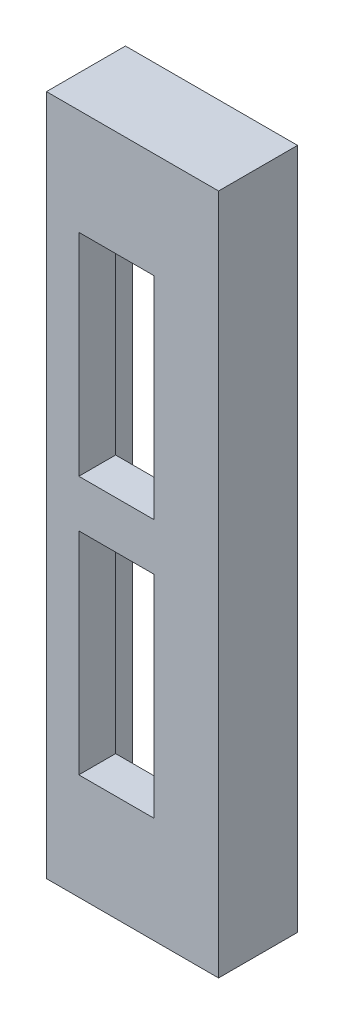
SolidWorks part; units mm, degrees
ref_plane "Front Plane" through (0, 0, 0) normal (0, 0, 1) x (1, 0, 0)
ref_plane "Top Plane" through (0, 0, 0) normal (0, 1, 0) x (1, 0, 0)
ref_plane "Right Plane" through (0, 0, 0) normal (1, 0, 0) x (0, 0, -1)
sketch "Sketch1" plane through (0, 0, 0) normal (0, 0, 1) x (1, 0, 0)
  line L4 (40, -50) -> (-40, -50)
  line L5 (40, 50) -> (40, -50)
  line L6 (-40, 50) -> (40, 50)
  line L7 (-40, -50) -> (-40, 50)
  line L8 (-39.25, -49.25) -> (-39.25, 49.25)
  line L9 (-39.25, 49.25) -> (39.25, 49.25)
  line L10 (39.25, 49.25) -> (39.25, -49.25)
  line L11 (39.25, -49.25) -> (-39.25, -49.25)
  line L12 (-16.5, 44.5) -> (-19.05, 38.013)
  line L13 (-16.5, 44.5) -> (16.5, 44.5)
  line L14 (16.5, 44.5) -> (19.05, 38.013)
  line L15 (-1000, 38.013) -> (49000, 38.013) construction
  line L16 (16.5, 31.526) -> (19.05, 38.013)
  line L17 (-16.5, 31.526) -> (16.5, 31.526)
  line L18 (-16.5, 31.526) -> (-19.05, 38.013)
  line L19 (-1000, 0.0306) -> (-26.3532, 0.0306) construction
  line L26 (-15.5, 43.5) -> (15.5, 43.5)
  line L27 (15.5, 43.5) -> (15.5, 32.5)
  line L28 (15.5, 32.5) -> (-15.5, 32.5)
  line L29 (-15.5, 32.5) -> (-15.5, 43.5)
  line L30 (15.5, -32.4388) -> (-15.5, -32.4388)
  line L31 (15.5, -43.4388) -> (15.5, -32.4388)
  line L32 (-15.5, -43.4388) -> (15.5, -43.4388)
  line L33 (-15.5, -32.4388) -> (-15.5, -43.4388)
  line L34 (-16.5, -31.4648) -> (16.5, -31.4648)
  line L35 (-16.5, -31.4648) -> (-19.05, -37.9518)
  line L36 (-16.5, -44.4388) -> (-19.05, -37.9518)
  line L37 (-16.5, -44.4388) -> (16.5, -44.4388)
  line L38 (16.5, -44.4388) -> (19.05, -37.9518)
  line L39 (16.5, -31.4648) -> (19.05, -37.9518)
  line L40 (-19.05, 0.0306) -> (-16.5, 6.5)
  line L41 (-16.5, 6.5) -> (16.5, 6.5)
  line L42 (16.5, 6.5) -> (19.05, 0.0306)
  line L43 (-15.5, 5.5) -> (-15.5, -5.5)
  line L44 (-15.5, -5.5) -> (15.5, -5.5)
  line L45 (15.5, -5.5) -> (15.5, 5.5)
  line L46 (15.5, 5.5) -> (-15.5, 5.5)
  line L47 (16.5, -6.4388) -> (19.05, 0.0306)
  line L48 (-16.5, -6.4388) -> (16.5, -6.4388)
  line L49 (-19.05, 0.0306) -> (-16.5, -6.4388)
  line L50 (-31.5, 35.5) -> (-25.0832, 38.05)
  line L51 (-25.0832, 38.05) -> (-18.5, 35.5)
  line L52 (-18.5, 35.5) -> (-18.5, 2.5)
  line L53 (-18.5, 2.5) -> (-23.8468, 0.429)
  line L55 (-31.5, 2.5) -> (-31.5, 35.5)
  line L56 (0, -999.9694) -> (0, 49000.0306) construction
  line L57 (-30.5, 34.5) -> (-19.5, 34.5)
  line L58 (-19.5, 34.5) -> (-19.5, 3.5)
  line L59 (-19.5, 3.5) -> (-30.5, 3.5)
  line L60 (-30.5, 3.5) -> (-30.5, 34.5)
  line L62 (18.5, 2.5) -> (23.8468, 0.429)
  line L63 (18.5, 35.5) -> (18.5, 2.5)
  line L64 (25.0832, 38.05) -> (18.5, 35.5)
  line L65 (31.5, 35.5) -> (25.0832, 38.05)
  line L66 (31.5, 2.5) -> (31.5, 35.5)
  line L67 (19.5, 3.5) -> (30.5, 3.5)
  line L68 (19.5, 34.5) -> (19.5, 3.5)
  line L69 (30.5, 34.5) -> (19.5, 34.5)
  line L70 (30.5, 3.5) -> (30.5, 34.5)
  line L71 (19.5, -34.4388) -> (19.5, -3.4388)
  line L72 (30.5, -34.4388) -> (19.5, -34.4388)
  line L73 (30.5, -3.4388) -> (30.5, -34.4388)
  line L74 (19.5, -3.4388) -> (30.5, -3.4388)
  line L75 (18.5, -2.4388) -> (23.8468, -0.3677)
  line L76 (18.5, -35.4388) -> (18.5, -2.4388)
  line L77 (25.0832, -37.9888) -> (18.5, -35.4388)
  line L78 (31.5, -35.4388) -> (25.0832, -37.9888)
  line L79 (31.5, -2.4388) -> (31.5, -35.4388)
  line L81 (-19.5, -3.4388) -> (-30.5, -3.4388)
  line L82 (-19.5, -34.4388) -> (-19.5, -3.4388)
  line L83 (-30.5, -34.4388) -> (-19.5, -34.4388)
  line L84 (-30.5, -3.4388) -> (-30.5, -34.4388)
  line L86 (-18.5, -2.4388) -> (-23.8468, -0.3677)
  line L87 (-18.5, -35.4388) -> (-18.5, -2.4388)
  line L88 (-25.0832, -37.9888) -> (-18.5, -35.4388)
  line L89 (-31.5, -35.4388) -> (-25.0832, -37.9888)
  line L90 (-31.5, -2.4388) -> (-31.5, -35.4388)
  line L91 (-25.0832, 0.1112) -> (-25.0832, 0.0306) construction
  line L92 (23.8468, -0.3677) -> (23.6168, 0.0306)
  line L93 (-23.6168, 0.0306) -> (-23.8468, 0.429)
  line L95 (-26.3139, 0.4391) -> (-26.5497, 0.0306)
  line L96 (-26.5497, 0.0306) -> (-26.3139, -0.3778)
  line L98 (-23.8468, -0.3677) -> (-23.6168, 0.0306)
  line L100 (26.5497, 0.0306) -> (26.3139, -0.3778)
  line L101 (26.3139, 0.4391) -> (26.5497, 0.0306)
  line L103 (23.6168, 0.0306) -> (23.8468, 0.429)
  line L104 (-26.3139, -0.3778) -> (-31.5, -2.4388)
  line L105 (-25.0832, -1.2394) -> (-24.35, -1.2394) [skipped]
  line L107 (-23.8132, 0.0306) -> (49000, 0.0306) construction
  line L110 (-26.3139, 0.4391) -> (-31.5, 2.5)
  line L111 (-24.35, 1.3006) -> (-25.0832, 1.3006) [skipped]
  line L113 (26.3139, -0.3778) -> (31.5, -2.4388)
  line L114 (26.3139, 0.4391) -> (31.5, 2.5)
  arc A0 (-23.8132, 0.0306) -> (-23.8739, 0.4184) centre (-25.0832, 0.0306) ccw construction
  arc A1 (-26.2891, 0.4292) -> (-26.2891, -0.3679) centre (-25.0832, 0.0306) ccw construction
  point P0 (-25.0832, -19)
  point P2 (24.5348, -19.0864)
  point P6 (0, 0)
  point P8 (25.0842, 19)
  point P10 (-25.0832, 19)
  point P12 (0, 38.013)
  dimension "D6" = 2.54
  dimension "D2" = 19.05
  dimension "D3" = 38.1
  dimension "D4" = 19.05
  dimension "D1" = 0.75
extrude "Boss-Extrude1" add sketch "Sketch1" along normal blind 3.81 contours L110 L95 L96 L104 L90 L89 L88 L87 L86 L98 L93 L53 L52 L51 L50 L55 L84 L81 L82 L83 L59 L60 L57 L58 | L40 L49 L48 L47 L42 L41 L46 L45 L44 L43 | L101 L114 L66 L65 L64 L63 L62 L103 L92 L75 L76 L77 L78 L79 L113 L100 L70 L67 L68 L69 L71 L74 L73 L72 | L18 L17 L16 L14 L13 L12 L28 L29 L26 L27 | L39 L34 L35 L36 L37 L38 L33 L30 L31 L32 | L7 L4 L5 L6 L10 L11 L8 L9
sketch "Sketch3" plane through (0, 0, 3.81) normal (0, 0, 1) x (1, 0, 0)
  line L0 (15.5, -43.4388) -> (15.5, -32.4388) construction
  line L1 (-15.5, -43.4388) -> (15.5, -43.4388) construction
  line L2 (-15.5, -32.4388) -> (-15.5, -43.4388) construction
  line L3 (15.5, -32.4388) -> (-15.5, -32.4388) construction
  line L4 (15.5, -5.5) -> (15.5, 5.5) construction
  line L5 (-15.5, -5.5) -> (15.5, -5.5) construction
  line L6 (-15.5, 5.5) -> (-15.5, -5.5) construction
  line L7 (15.5, 5.5) -> (-15.5, 5.5) construction
  line L8 (-30.5, -34.4388) -> (-19.5, -34.4388) construction
  line L9 (-19.5, -34.4388) -> (-19.5, -3.4388) construction
  line L10 (-30.5, -3.4388) -> (-30.5, -34.4388) construction
  line L11 (-19.5, -3.4388) -> (-30.5, -3.4388) construction
  line L12 (-19.5, 3.5) -> (-30.5, 3.5) construction
  line L13 (-19.5, 34.5) -> (-19.5, 3.5) construction
  line L14 (-30.5, 3.5) -> (-30.5, 34.5) construction
  line L15 (-30.5, 34.5) -> (-19.5, 34.5) construction
  line L16 (-15.5, 32.5) -> (-15.5, 43.5) construction
  line L17 (15.5, 32.5) -> (-15.5, 32.5) construction
  line L18 (15.5, 43.5) -> (15.5, 32.5) construction
  line L19 (-15.5, 43.5) -> (15.5, 43.5) construction
  line L20 (19.5, 3.5) -> (30.5, 3.5) construction
  line L21 (30.5, 3.5) -> (30.5, 34.5) construction
  line L22 (30.5, 34.5) -> (19.5, 34.5) construction
  line L23 (19.5, 34.5) -> (19.5, 3.5) construction
  line L24 (30.5, -34.4388) -> (19.5, -34.4388) construction
  line L25 (30.5, -3.4388) -> (30.5, -34.4388) construction
  line L26 (19.5, -34.4388) -> (19.5, -3.4388) construction
  line L27 (19.5, -3.4388) -> (30.5, -3.4388) construction
  line L28 (40, -50) -> (-40, -50) construction
  line L29 (40, 50) -> (40, -50) construction
  line L30 (-40, 50) -> (40, 50) construction
  line L31 (-40, -50) -> (-40, 50) construction
  line L32 (15.5, -43.4388) -> (15.5, -32.4388)
  line L33 (-15.5, -43.4388) -> (15.5, -43.4388)
  line L34 (-15.5, -32.4388) -> (-15.5, -43.4388)
  line L35 (15.5, -32.4388) -> (-15.5, -32.4388)
  line L36 (15.5, -5.5) -> (15.5, 5.5)
  line L37 (-15.5, -5.5) -> (15.5, -5.5)
  line L38 (-15.5, 5.5) -> (-15.5, -5.5)
  line L39 (15.5, 5.5) -> (-15.5, 5.5)
  line L40 (-30.5, -34.4388) -> (-19.5, -34.4388)
  line L41 (-19.5, -34.4388) -> (-19.5, -3.4388)
  line L42 (-30.5, -3.4388) -> (-30.5, -34.4388)
  line L43 (-19.5, -3.4388) -> (-30.5, -3.4388)
  line L44 (-19.5, 3.5) -> (-30.5, 3.5)
  line L45 (-19.5, 34.5) -> (-19.5, 3.5)
  line L46 (-30.5, 3.5) -> (-30.5, 34.5)
  line L47 (-30.5, 34.5) -> (-19.5, 34.5)
  line L48 (-15.5, 32.5) -> (-15.5, 43.5)
  line L49 (15.5, 32.5) -> (-15.5, 32.5)
  line L50 (15.5, 43.5) -> (15.5, 32.5)
  line L51 (-15.5, 43.5) -> (15.5, 43.5)
  line L52 (19.5, 3.5) -> (30.5, 3.5)
  line L53 (30.5, 3.5) -> (30.5, 34.5)
  line L54 (30.5, 34.5) -> (19.5, 34.5)
  line L55 (19.5, 34.5) -> (19.5, 3.5)
  line L56 (30.5, -34.4388) -> (19.5, -34.4388)
  line L57 (30.5, -3.4388) -> (30.5, -34.4388)
  line L58 (19.5, -34.4388) -> (19.5, -3.4388)
  line L59 (19.5, -3.4388) -> (30.5, -3.4388)
  line L60 (40, -50) -> (-40, -50)
  line L61 (40, 50) -> (40, -50)
  line L62 (-40, 50) -> (40, 50)
  line L63 (-40, -50) -> (-40, 50)
extrude "Boss-Extrude2" add sketch "Sketch3" along normal blind 1.5875
fillet "Fillet1" radius 0.05 4 edges at (39.25, -49.25, 1.905) (-39.25, -49.25, 1.905) (-39.25, 49.25, 1.905) (39.25, 49.25, 1.905)
sketch "Sketch4" plane through (0, 0, 0) normal (0, 0, -1) x (-1, 0, 0)
  line L0 (-39.2, -49.25) -> (39.2, -49.25) construction
  line L1 (39.25, -49.2) -> (39.25, 49.2) construction
  line L2 (39.2, 49.25) -> (-39.2, 49.25) construction
  line L3 (-39.25, 49.2) -> (-39.25, -49.2) construction
  line L4 (40, -50) -> (40, 50)
  line L5 (40, 50) -> (-40, 50)
  line L6 (-40, 50) -> (-40, -50)
  line L7 (-40, -50) -> (40, -50)
  line L8 (40, -50) -> (40, 50)
  line L9 (40, 50) -> (-40, 50)
  line L10 (-40, 50) -> (-40, -50)
  line L11 (-40, -50) -> (40, -50)
  line L12 (-39.2, -49.25) -> (39.2, -49.25)
  line L13 (39.25, -49.2) -> (39.25, 49.2)
  line L14 (39.2, 49.25) -> (-39.2, 49.25)
  line L15 (-39.25, 49.2) -> (-39.25, -49.2)
  arc A0 (-39.25, -49.2) -> (-39.2, -49.25) centre (-39.2, -49.2) ccw construction
  arc A1 (39.2, -49.25) -> (39.25, -49.2) centre (39.2, -49.2) ccw construction
  arc A2 (39.25, 49.2) -> (39.2, 49.25) centre (39.2, 49.2) ccw construction
  arc A3 (-39.2, 49.25) -> (-39.25, 49.2) centre (-39.2, 49.2) ccw construction
  arc A4 (-39.25, -49.2) -> (-39.2, -49.25) centre (-39.2, -49.2) ccw
  arc A5 (39.2, -49.25) -> (39.25, -49.2) centre (39.2, -49.2) ccw
  arc A6 (39.25, 49.2) -> (39.2, 49.25) centre (39.2, 49.2) ccw
  arc A7 (-39.2, 49.25) -> (-39.25, 49.2) centre (-39.2, 49.2) ccw
  dimension "D1" = 0
extrude "Boss-Extrude3" add sketch "Sketch4" along normal blind 6.191
sketch "Sketch5" plane through (0, 0, 3.81) normal (0, 0, -1) x (-1, 0, 0)
  line L1 (-14.75, 52.8593) -> (41.8787, 52.8593)
  line L2 (-14.75, 52.8593) -> (-14.75, -53.464)
  line L3 (-14.75, -53.464) -> (41.8787, -53.464)
  line L4 (41.8787, 52.8593) -> (41.8787, -53.464)
  line L5 (-14.75, 49.75) -> (-14.75, -50.25) construction
  line L6 (-14.75, 49.75) -> (-14.75, -50.25) construction
extrude "Cut-Extrude1" cut sketch "Sketch5" against normal through all both and the other way through all
sketch "Sketch6" plane through (0, 0, 0) normal (0, 0, -1) x (-1, 0, 0)
  line L0 (-16.5, -44.4388) -> (-14.75, -44.4388) construction
  line L1 (-14.75, -44.4388) -> (-14.75, -43.4388) construction
  line L2 (-14.75, -43.4388) -> (-15.5, -43.4388) construction
  line L3 (-15.5, -43.4388) -> (-15.5, -32.4388) construction
  line L4 (-15.5, -32.4388) -> (-14.75, -32.4388) construction
  line L5 (-14.75, -32.4388) -> (-14.75, -31.4648) construction
  line L6 (-14.75, -31.4648) -> (-16.5, -31.4648) construction
  line L7 (-16.5, -31.4648) -> (-19.05, -37.9518) construction
  line L8 (-19.05, -37.9518) -> (-16.5, -44.4388) construction
  line L9 (-16.5, -6.4388) -> (-14.75, -6.4388) construction
  line L10 (-14.75, -6.4388) -> (-14.75, -5.5) construction
  line L11 (-14.75, -5.5) -> (-15.5, -5.5) construction
  line L12 (-15.5, -5.5) -> (-15.5, 5.5) construction
  line L13 (-15.5, 5.5) -> (-14.75, 5.5) construction
  line L14 (-14.75, 5.5) -> (-14.75, 6.5) construction
  line L15 (-14.75, 6.5) -> (-16.5, 6.5) construction
  line L16 (-16.5, 6.5) -> (-19.05, 0.0306) construction
  line L17 (-19.05, 0.0306) -> (-16.5, -6.4388) construction
  line L18 (-16.5, 31.526) -> (-14.75, 31.526) construction
  line L19 (-14.75, 31.526) -> (-14.75, 32.5) construction
  line L20 (-14.75, 32.5) -> (-15.5, 32.5) construction
  line L21 (-15.5, 32.5) -> (-15.5, 43.5) construction
  line L22 (-15.5, 43.5) -> (-14.75, 43.5) construction
  line L23 (-14.75, 43.5) -> (-14.75, 44.5) construction
  line L24 (-14.75, 44.5) -> (-16.5, 44.5) construction
  line L25 (-16.5, 44.5) -> (-19.05, 38.013) construction
  line L26 (-19.05, 38.013) -> (-16.5, 31.526) construction
  line L27 (-16.5, -44.4388) -> (-14.75, -44.4388)
  line L28 (-14.75, -44.4388) -> (-14.75, -43.4388)
  line L29 (-14.75, -43.4388) -> (-15.5, -43.4388)
  line L30 (-15.5, -43.4388) -> (-15.5, -32.4388)
  line L31 (-15.5, -32.4388) -> (-14.75, -32.4388)
  line L32 (-14.75, -32.4388) -> (-14.75, -31.4648)
  line L33 (-14.75, -31.4648) -> (-16.5, -31.4648)
  line L34 (-16.5, -31.4648) -> (-19.05, -37.9518)
  line L35 (-19.05, -37.9518) -> (-16.5, -44.4388)
  line L36 (-16.5, -6.4388) -> (-14.75, -6.4388)
  line L37 (-14.75, -6.4388) -> (-14.75, -5.5)
  line L38 (-14.75, -5.5) -> (-15.5, -5.5)
  line L39 (-15.5, -5.5) -> (-15.5, 5.5)
  line L40 (-15.5, 5.5) -> (-14.75, 5.5)
  line L41 (-14.75, 5.5) -> (-14.75, 6.5)
  line L42 (-14.75, 6.5) -> (-16.5, 6.5)
  line L43 (-16.5, 6.5) -> (-19.05, 0.0306)
  line L44 (-19.05, 0.0306) -> (-16.5, -6.4388)
  line L45 (-16.5, 31.526) -> (-14.75, 31.526)
  line L46 (-14.75, 31.526) -> (-14.75, 32.5)
  line L47 (-14.75, 32.5) -> (-15.5, 32.5)
  line L48 (-15.5, 32.5) -> (-15.5, 43.5)
  line L49 (-15.5, 43.5) -> (-14.75, 43.5)
  line L50 (-14.75, 43.5) -> (-14.75, 44.5)
  line L51 (-14.75, 44.5) -> (-16.5, 44.5)
  line L52 (-16.5, 44.5) -> (-19.05, 38.013)
  line L53 (-19.05, 38.013) -> (-16.5, 31.526)
extrude "Cut-Extrude2" cut sketch "Sketch6" against normal up to surface (3.81 mm away) up to face at (20.5272, 0.0219, 3.81)
sketch "Sketch7" plane through (15.5, 0, 0) normal (-1, 0, 0) x (0, 0, 1)
  line L0 (5.3975, 43.5) -> (3.81, 43.5) construction
  line L1 (3.81, 43.5) -> (3.81, 32.5) construction
  line L2 (3.81, 32.5) -> (5.3975, 32.5) construction
  line L3 (5.3975, 32.5) -> (5.3975, 43.5) construction
  line L4 (5.3975, 5.5) -> (3.81, 5.5) construction
  line L5 (3.81, 5.5) -> (3.81, -5.5) construction
  line L6 (3.81, -5.5) -> (5.3975, -5.5) construction
  line L7 (5.3975, -5.5) -> (5.3975, 5.5) construction
  line L8 (5.3975, -32.4388) -> (3.81, -32.4388) construction
  line L9 (3.81, -32.4388) -> (3.81, -43.4388) construction
  line L10 (3.81, -43.4388) -> (5.3975, -43.4388) construction
  line L11 (5.3975, -43.4388) -> (5.3975, -32.4388) construction
  line L12 (5.3975, 43.5) -> (3.81, 43.5)
  line L13 (3.81, 43.5) -> (3.81, 32.5)
  line L14 (3.81, 32.5) -> (5.3975, 32.5)
  line L15 (5.3975, 32.5) -> (5.3975, 43.5)
  line L16 (5.3975, 5.5) -> (3.81, 5.5)
  line L17 (3.81, 5.5) -> (3.81, -5.5)
  line L18 (3.81, -5.5) -> (5.3975, -5.5)
  line L19 (5.3975, -5.5) -> (5.3975, 5.5)
  line L20 (5.3975, -32.4388) -> (3.81, -32.4388)
  line L21 (3.81, -32.4388) -> (3.81, -43.4388)
  line L22 (3.81, -43.4388) -> (5.3975, -43.4388)
  line L23 (5.3975, -43.4388) -> (5.3975, -32.4388)
extrude "Boss-Extrude4" add sketch "Sketch7" along normal up to surface (0.75 mm away) up to face at (14.75, -47.5629, 1.0055)
sketch "Sketch8" plane through (14.75, 0, 0) normal (-1, 0, 0) x (0, 0, 1)
  line L1 (-6.191, 50) -> (5.3975, 50)
  line L2 (-6.191, 50) -> (-6.191, -50)
  line L3 (-6.191, -50) -> (5.3975, -50)
  line L4 (5.3975, 50) -> (5.3975, -50)
extrude "Boss-Extrude5" add sketch "Sketch8" against normal blind 1
